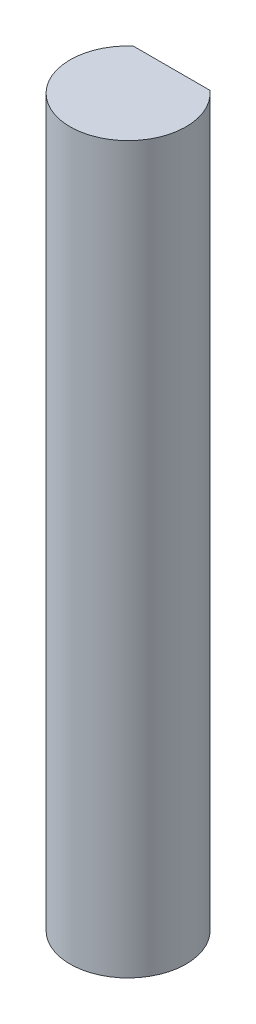
SolidWorks part; units mm, degrees
ref_plane "Front Plane" through (0, 0, 0) normal (0, 0, 1) x (1, 0, 0)
ref_plane "Top Plane" through (0, 0, 0) normal (0, 1, 0) x (1, 0, 0)
ref_plane "Right Plane" through (0, 0, 0) normal (1, 0, 0) x (0, 0, -1)
sketch "Sketch1" plane through (0, 0, 0) normal (0, 1, 0) x (1, 0, 0)
  line L0 (-1.3229, 1.5) -> (1.3229, 1.5)
  arc A0 (-1.3229, 1.5) -> (1.3229, 1.5) centre (0, 0) ccw
  dimension "D1" = 1.5
  dimension "D2" = 2
extrude "Boss-Extrude1" add sketch "Sketch1" along normal blind 25
equation "\"length\" = 25"
equation "\"D1@Boss-Extrude1\"=\"length\""
